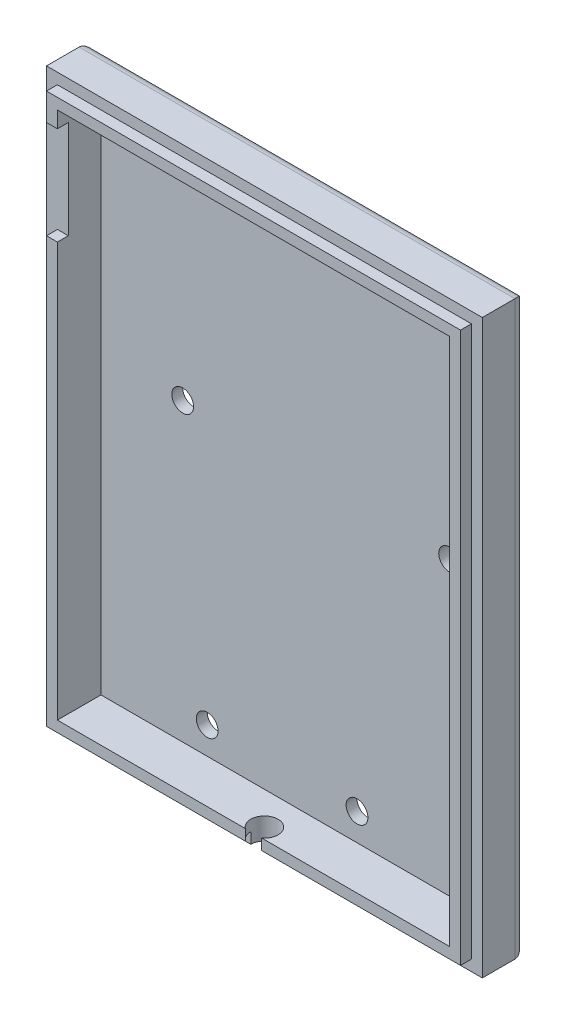
SolidWorks part; units mm, degrees
ref_plane "Front Plane" through (0, 0, 0) normal (0, 0, 1) x (1, 0, 0)
ref_plane "Top Plane" through (0, 0, 0) normal (0, 1, 0) x (1, 0, 0)
ref_plane "Right Plane" through (0, 0, 0) normal (1, 0, 0) x (0, 0, -1)
sketch "Sketch1" plane through (0, 0, 0) normal (0, 0, 1) x (1, 0, 0)
  line L1 (-5, 38.5345) -> (75, 38.5345)
  line L2 (-5, 38.5345) -> (-5, -66.4655)
  line L3 (-5, -66.4655) -> (75, -66.4655)
  line L4 (75, 38.5345) -> (75, -66.4655)
  line L5 (7, 8.8494) -> (67, 8.8494)
  line L6 (7, 8.8494) -> (7, -62.4655)
  line L7 (7, -62.4655) -> (67, -62.4655)
  line L8 (67, 8.8494) -> (67, -62.4655)
  circle A0 centre (63, -8.9506) radius 2
  circle A1 centre (46, -57.4655) radius 2
  circle A2 centre (18.5, -57.4655) radius 2
  circle A3 centre (14, -8.1506) radius 2
  dimension "D6" = 4
  dimension "D7" = 4
  dimension "D9" = 4
  dimension "D14" = 4
  dimension "D15" = 4
  dimension "D1" = 105
  dimension "D2" = 80
  dimension "D3" = 60
  dimension "D4" = 4
  dimension "D5" = 12
  dimension "D8" = 17.8
  dimension "D10" = 5
  dimension "D11" = 21
  dimension "D12" = 27.5
  dimension "D13" = 11.5
  dimension "D16" = 17
  dimension "D17" = 7
extrude "Boss-Extrude2" add sketch "Sketch1" along normal blind 8 contours L4 L1 L2 L3 L5 L8 L7 L6 | L8 L5 L6 L7 A3 A2 A1 A0
sketch "Sketch2" plane through (0, 0, 8) normal (0, 0, 1) x (1, 0, 0)
  line L0 (-5, 38.5345) -> (-5, -66.4655) construction
  line L1 (-1, 34.5345) -> (71, 34.5345)
  line L2 (-1, 34.5345) -> (-1, -62.4655)
  line L3 (-1, -62.4655) -> (71, -62.4655)
  line L4 (71, 34.5345) -> (71, -62.4655)
  line L5 (-5, -66.4655) -> (75, -66.4655) construction
  line L6 (75, 38.5345) -> (75, -66.4655) construction
  line L7 (-5, 38.5345) -> (75, 38.5345) construction
  dimension "D1" = 4
  dimension "D2" = 4
  dimension "D3" = 4
  dimension "D4" = 4
extrude "Cut-Extrude1" cut sketch "Sketch2" against normal blind 6 contours L2 L1 L4 L3
sketch "Sketch3" plane through (0, 0, 8) normal (0, 0, 1) x (1, 0, 0)
  line L0 (-1, 34.5345) -> (-1, -62.4655) construction
  line L1 (-3, 36.5345) -> (73, 36.5345)
  line L2 (-3, 36.5345) -> (-3, -64.4655)
  line L3 (-3, -64.4655) -> (73, -64.4655)
  line L4 (73, 36.5345) -> (73, -64.4655)
  line L5 (-5, 38.5345) -> (75, 38.5345) construction
  line L6 (75, 38.5345) -> (75, -66.4655) construction
  line L7 (-5, -66.4655) -> (75, -66.4655) construction
  dimension "D1" = 2
  dimension "D2" = 2
  dimension "D3" = 2
  dimension "D4" = 2
extrude "Boss-Extrude3" add sketch "Sketch3" along normal blind 2
sketch "Sketch4" plane through (0, 0, 10) normal (0, 0, 1) x (1, 0, 0)
  line L0 (-3, 36.5345) -> (-3, -64.4655) construction
  line L1 (-1, 34.5345) -> (71, 34.5345)
  line L2 (-1, 34.5345) -> (-1, -62.4655)
  line L3 (-1, -62.4655) -> (71, -62.4655)
  line L4 (71, 34.5345) -> (71, -62.4655)
  line L5 (-3, -64.4655) -> (73, -64.4655) construction
  line L6 (73, -64.4655) -> (73, 36.5345) construction
  line L8 (73, 36.5345) -> (-3, 36.5345) construction
  dimension "D1" = 2
  dimension "D2" = 2
  dimension "D3" = 2
  dimension "D4" = 2
extrude "Cut-Extrude2" cut sketch "Sketch4" against normal blind 2 contours L2 L1 L4 L3
sketch "Sketch5" plane through (0, -66.4655, 0) normal (0, -1, 0) x (-1, 0, 0)
  line L0 (5, -8) -> (-75, -8) construction
  circle A0 centre (-35, -8) radius 2.5
  dimension "D1" = 5
extrude "Cut-Extrude3" cut sketch "Sketch5" against normal blind 5
fillet "Fillet1" radius 2 4 edges at (35, -66.4655, 0) (-5, -13.9655, 0) (35, 38.5345, 0) (75, -13.9655, 0)
sketch "Sketch6" plane through (0, 0, 10) normal (0, 0, 1) x (1, 0, 0)
  line L0 (-3, 36.5345) -> (-3, -64.4655) construction
  line L1 (-3, 31.5345) -> (-1, 31.5345)
  line L2 (-3, 31.5345) -> (-3, 13.5345)
  line L3 (-3, 13.5345) -> (-1, 13.5345)
  line L4 (-1, 31.5345) -> (-1, 13.5345)
  line L5 (-1, 34.5345) -> (-1, -62.4655) construction
  line L7 (73, 36.5345) -> (-3, 36.5345) construction
  dimension "D1" = 18
  dimension "D2" = 5
extrude "Cut-Extrude4" cut sketch "Sketch6" against normal blind 2
